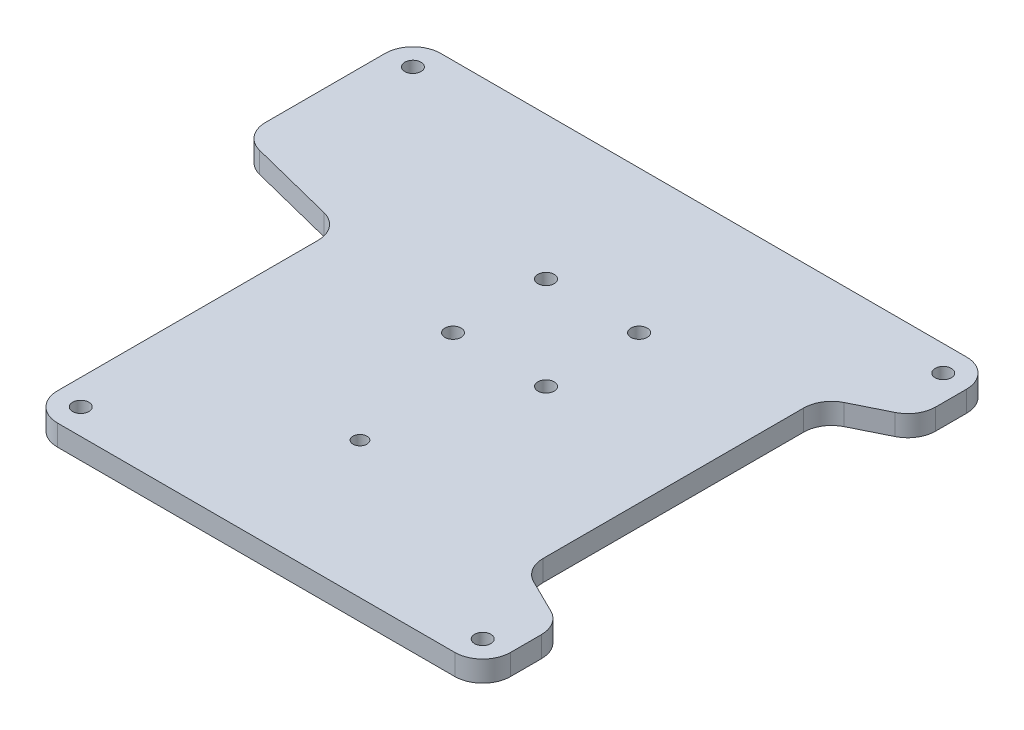
SolidWorks part; units mm, degrees
ref_plane "Front Plane" through (0, 0, 0) normal (0, 0, 1) x (1, 0, 0)
ref_plane "Top Plane" through (0, 0, 0) normal (0, 1, 0) x (1, 0, 0)
ref_plane "Right Plane" through (0, 0, 0) normal (1, 0, 0) x (0, 0, -1)
sketch "Sketch1" plane through (0, 0, 0) normal (0, 1, 0) x (1, 0, 0)
  line L0 (-41.7, 0) -> (41.7, 0) construction
  line L1 (-35.7, -55) -> (49.7, -55)
  line L2 (55.7, -49) -> (55.7, -42.3778)
  line L3 (52.3607, -37) -> (45.0393, -33.3778)
  line L4 (41.7, -28) -> (41.7, 28)
  line L5 (45.0393, 33.3778) -> (52.3607, 37)
  line L6 (55.7, 42.3778) -> (55.7, 49)
  line L7 (49.7, 55) -> (-63.3, 55)
  line L8 (-69.3, 49) -> (-69.3, 23.3173)
  line L9 (-64.7694, 17.5) -> (-46.2306, 12.8173)
  line L10 (-41.7, 7) -> (-41.7, -49)
  line L11 (-36.8, 20.5) -> (23.2, 20.5) construction
  line L12 (34.04, -3.15) -> (35.74, -3.15) construction
  line L13 (34.04, -3.15) -> (34.04, 3.15) construction
  line L14 (34.04, 3.15) -> (35.74, 3.15) construction
  line L15 (35.74, -3.15) -> (35.74, 3.15) construction
  line L16 (34.04, -3.15) -> (35.74, 3.15) construction
  line L17 (34.04, 3.15) -> (35.74, -3.15) construction
  line L18 (-33.5, -3.15) -> (-31.8, -3.15) construction
  line L19 (-33.5, -3.15) -> (-33.5, 3.15) construction
  line L20 (-33.5, 3.15) -> (-31.8, 3.15) construction
  line L21 (-31.8, -3.15) -> (-31.8, 3.15) construction
  line L22 (-33.5, -3.15) -> (-31.8, 3.15) construction
  line L23 (-33.5, 3.15) -> (-31.8, -3.15) construction
  line L24 (23.2, 20.5) -> (41.7, 20.5) construction
  line L25 (-41.7, -20) -> (-6.7, -20) construction
  line L26 (-6.7, -20) -> (-6.7, -55) construction
  line L27 (50.2, 55) -> (50.2, 49.5) construction
  line L28 (50.2, 49.5) -> (55.7, 49.5) construction
  line L29 (-63.8, 55) -> (-63.8, 49.5) construction
  line L30 (-63.8, 49.5) -> (-69.3, 49.5) construction
  line L31 (-41.7, -49.5) -> (-36.2, -49.5) construction
  line L32 (-36.2, -49.5) -> (-36.2, -55) construction
  line L33 (50.2, -55) -> (50.2, -49.5) construction
  line L34 (50.2, -49.5) -> (55.7, -49.5) construction
  line L35 (0, 14.3181) -> (0, 0) construction
  line L36 (-10, 4.3181) -> (10, 4.3181) construction
  line L37 (-10, 4.3181) -> (-10, 24.3181) construction
  line L38 (-10, 24.3181) -> (10, 24.3181) construction
  line L39 (10, 4.3181) -> (10, 24.3181) construction
  line L40 (-10, 4.3181) -> (10, 24.3181) construction
  line L41 (-10, 24.3181) -> (10, 4.3181) construction
  line L42 (0, 0) -> (0, -25.6819) construction
  arc A0 (49.7, -55) -> (55.7, -49) centre (49.7, -49) ccw
  arc A1 (55.7, -42.3778) -> (52.3607, -37) centre (49.7, -42.3778) ccw
  arc A2 (45.0393, -33.3778) -> (41.7, -28) centre (47.7, -28) cw
  arc A3 (41.7, 28) -> (45.0393, 33.3778) centre (47.7, 28) cw
  arc A4 (52.3607, 37) -> (55.7, 42.3778) centre (49.7, 42.3778) ccw
  arc A5 (55.7, 49) -> (49.7, 55) centre (49.7, 49) ccw
  arc A6 (-63.3, 55) -> (-69.3, 49) centre (-63.3, 49) ccw
  arc A7 (-69.3, 23.3173) -> (-64.7694, 17.5) centre (-63.3, 23.3173) ccw
  arc A8 (-46.2306, 12.8173) -> (-41.7, 7) centre (-47.7, 7) cw
  arc A9 (-41.7, -49) -> (-35.7, -55) centre (-35.7, -49) ccw
  circle A10 centre (-63.8, 49.5) radius 1.75
  circle A11 centre (50.2, 49.5) radius 1.5 construction
  circle A12 centre (-36.2, -49.5) radius 1.75
  circle A13 centre (50.2, -49.5) radius 1.75
  circle A14 centre (-36.8, 20.5) radius 2.75 construction
  circle A15 centre (23.2, 20.5) radius 2.5 construction
  circle A16 centre (-6.7, -20) radius 2.75 construction
  circle A17 centre (23.2, 20.5) radius 2.75 construction
  circle A18 centre (50.2, 49.5) radius 1.75
  circle A19 centre (10, 24.3181) radius 1.5 construction
  circle A20 centre (-10, 24.3181) radius 1.75
  circle A21 centre (-10, 4.3181) radius 1.75
  circle A22 centre (10, 4.3181) radius 1.75
  circle A23 centre (10, 24.3181) radius 1.75
  circle A24 centre (0, -25.6819) radius 1.25 construction
  circle A25 centre (0, -25.6819) radius 1.5
  point P2 (0, 0)
  point P37 (41.7, 0)
  point P49 (34.89, 0)
  point P54 (-32.65, 0)
  point P74 (0, 0)
  dimension "D4" = 6
  dimension "D15" = 5
  dimension "D21" = 3
  dimension "D24" = 3
  dimension "D28" = 2.5
  dimension "D1" = 110
  dimension "D2" = 125
  dimension "D3" = 18
  dimension "D5" = 27
  dimension "D6" = 83.4
  dimension "D7" = 27.6
  dimension "D8" = 37.5
  dimension "D9" = 48
  dimension "D10" = 6.3
  dimension "D11" = 1.7
  dimension "D12" = 8.2
  dimension "D13" = 65.84
  dimension "D16" = 18.5
  dimension "D17" = 60
  dimension "D18" = 34.5
  dimension "D19" = 35
  dimension "D22" = 5.5
  dimension "D25" = 20
  dimension "D26" = 40
  dimension "D14" = 0.25
  dimension "D20" = 0.25
  dimension "D23" = 0.25
  dimension "D27" = 0.25
extrude "Boss-Extrude1" add sketch "Sketch1" along normal blind 4.5
equation "\"Tolerance\"=0.25"
equation "\"D14@Sketch1\"=\"Tolerance\""
equation "\"D20@Sketch1\"=\"Tolerance\""
equation "\"D23@Sketch1\"=\"Tolerance\""
equation "\"D27@Sketch1\"=\"Tolerance\""
